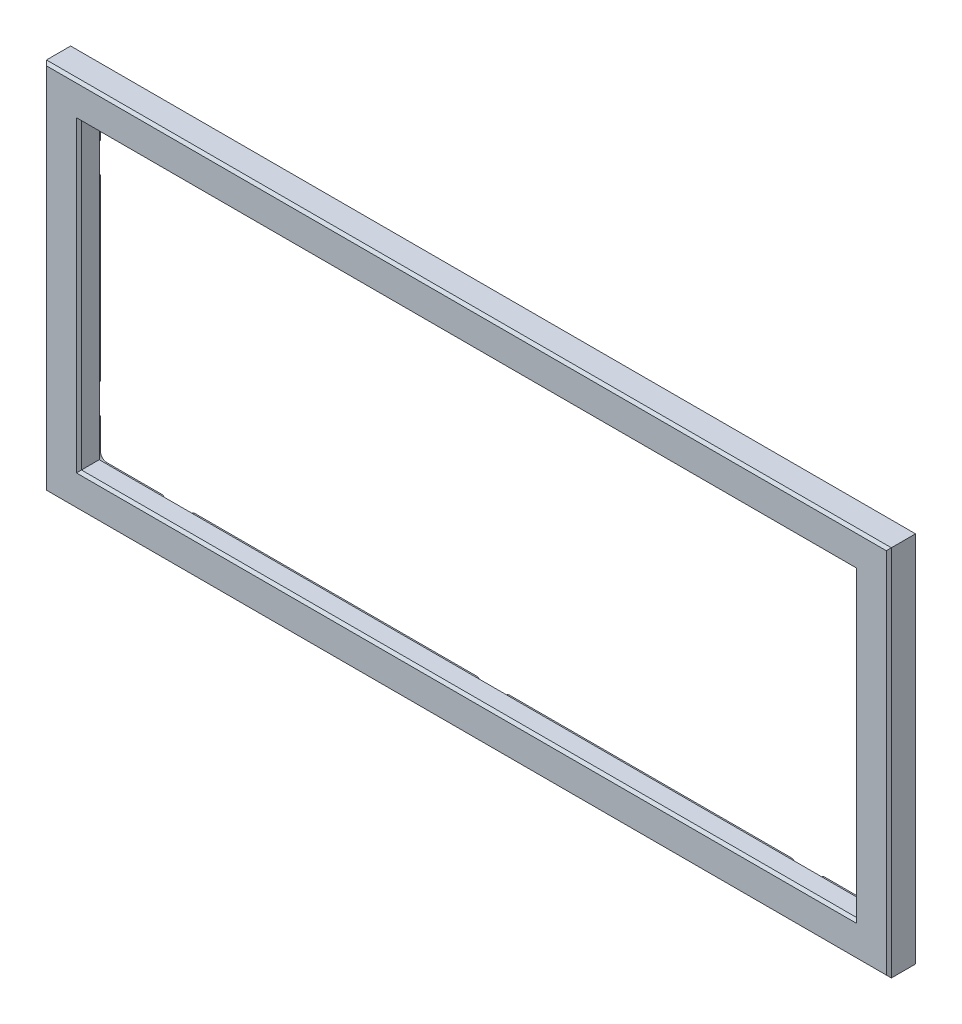
SolidWorks part; units mm, degrees
material "7075-T6 (SN)"
ref_plane "Front Plane" through (0, 0, 0) normal (0, 0, 1) x (1, 0, 0)
ref_plane "Top Plane" through (0, 0, 0) normal (0, 1, 0) x (1, 0, 0)
ref_plane "Right Plane" through (0, 0, 0) normal (1, 0, 0) x (0, 0, -1)
sketch "Sketch1" plane through (0, 0, 0) normal (0, 0, 1) x (1, 0, 0)
  line L43 (-4.2125, 142.325) -> (328.0625, 142.325)
  line L44 (-4.2125, 142.325) -> (-4.2125, -4.2125)
  line L45 (-4.2125, -4.2125) -> (328.0625, -4.2125)
  line L46 (328.0625, 142.325) -> (328.0625, -4.2125)
  line L104 (313.8, 130.5625) -> (292.3, 130.5625)
  line L105 (290.8, 132.0625) -> (290.8, 132.5625)
  line L106 (280.8, 132.5625) -> (280.8, 132.0625)
  line L107 (279.3, 130.5625) -> (168.425, 130.5625)
  line L108 (166.925, 132.0625) -> (166.925, 132.5625)
  line L109 (156.925, 132.5625) -> (156.925, 132.0625)
  line L110 (155.425, 130.5625) -> (44.55, 130.5625)
  line L111 (43.05, 132.0625) -> (43.05, 132.5625)
  line L112 (33.05, 132.5625) -> (33.05, 132.0625)
  line L113 (31.55, 130.5625) -> (10.05, 130.5625)
  line L114 (7.55, 128.0625) -> (7.55, 116.5625)
  line L115 (6.05, 115.0625) -> (5.55, 115.0625)
  line L116 (5.55, 105.0625) -> (6.05, 105.0625)
  line L117 (7.55, 103.5625) -> (7.55, 34.55)
  line L118 (6.05, 33.05) -> (5.55, 33.05)
  line L119 (5.55, 23.05) -> (6.05, 23.05)
  line L120 (7.55, 21.55) -> (7.55, 10.05)
  line L121 (10.05, 7.55) -> (31.55, 7.55)
  line L122 (33.05, 6.05) -> (33.05, 5.55)
  line L123 (43.05, 5.55) -> (43.05, 6.05)
  line L124 (44.55, 7.55) -> (155.425, 7.55)
  line L125 (156.925, 6.05) -> (156.925, 5.55)
  line L126 (166.925, 5.55) -> (166.925, 6.05)
  line L127 (168.425, 7.55) -> (279.3, 7.55)
  line L128 (280.8, 6.05) -> (280.8, 5.55)
  line L129 (290.8, 5.55) -> (290.8, 6.05)
  line L130 (292.3, 7.55) -> (313.8, 7.55)
  line L131 (316.3, 10.05) -> (316.3, 21.55)
  line L132 (317.8, 23.05) -> (318.3, 23.05)
  line L133 (318.3, 33.05) -> (317.8, 33.05)
  line L134 (316.3, 34.55) -> (316.3, 103.5625)
  line L135 (317.8, 105.0625) -> (318.3, 105.0625)
  line L136 (318.3, 115.0625) -> (317.8, 115.0625)
  line L137 (316.3, 116.5625) -> (316.3, 128.0625)
  line L138 (313.8, 130.5625) -> (292.3, 130.5625)
  line L139 (290.8, 132.0625) -> (290.8, 132.5625)
  line L140 (280.8, 132.5625) -> (280.8, 132.0625)
  line L141 (279.3, 130.5625) -> (168.425, 130.5625)
  line L142 (166.925, 132.0625) -> (166.925, 132.5625)
  line L143 (156.925, 132.5625) -> (156.925, 132.0625)
  line L144 (155.425, 130.5625) -> (44.55, 130.5625)
  line L145 (43.05, 132.0625) -> (43.05, 132.5625)
  line L146 (33.05, 132.5625) -> (33.05, 132.0625)
  line L147 (31.55, 130.5625) -> (10.05, 130.5625)
  line L148 (7.55, 128.0625) -> (7.55, 116.5625)
  line L149 (6.05, 115.0625) -> (5.55, 115.0625)
  line L150 (5.55, 105.0625) -> (6.05, 105.0625)
  line L151 (7.55, 103.5625) -> (7.55, 34.55)
  line L152 (6.05, 33.05) -> (5.55, 33.05)
  line L153 (5.55, 23.05) -> (6.05, 23.05)
  line L154 (7.55, 21.55) -> (7.55, 10.05)
  line L155 (10.05, 7.55) -> (31.55, 7.55)
  line L156 (33.05, 6.05) -> (33.05, 5.55)
  line L157 (43.05, 5.55) -> (43.05, 6.05)
  line L158 (44.55, 7.55) -> (155.425, 7.55)
  line L159 (156.925, 6.05) -> (156.925, 5.55)
  line L160 (166.925, 5.55) -> (166.925, 6.05)
  line L161 (168.425, 7.55) -> (279.3, 7.55)
  line L162 (280.8, 6.05) -> (280.8, 5.55)
  line L163 (290.8, 5.55) -> (290.8, 6.05)
  line L164 (292.3, 7.55) -> (313.8, 7.55)
  line L165 (316.3, 10.05) -> (316.3, 21.55)
  line L166 (317.8, 23.05) -> (318.3, 23.05)
  line L167 (318.3, 33.05) -> (317.8, 33.05)
  line L168 (316.3, 34.55) -> (316.3, 103.5625)
  line L169 (317.8, 105.0625) -> (318.3, 105.0625)
  line L170 (318.3, 115.0625) -> (317.8, 115.0625)
  line L171 (316.3, 116.5625) -> (316.3, 128.0625)
  arc A136 (290.8, 132.0625) -> (292.3, 130.5625) centre (292.3, 132.0625) ccw
  arc A137 (290.8, 132.5625) -> (280.8, 132.5625) centre (285.8, 132.5625) ccw
  arc A138 (279.3, 130.5625) -> (280.8, 132.0625) centre (279.3, 132.0625) ccw
  arc A139 (166.925, 132.0625) -> (168.425, 130.5625) centre (168.425, 132.0625) ccw
  arc A140 (166.925, 132.5625) -> (156.925, 132.5625) centre (161.925, 132.5625) ccw
  arc A141 (155.425, 130.5625) -> (156.925, 132.0625) centre (155.425, 132.0625) ccw
  arc A142 (43.05, 132.0625) -> (44.55, 130.5625) centre (44.55, 132.0625) ccw
  arc A143 (43.05, 132.5625) -> (33.05, 132.5625) centre (38.05, 132.5625) ccw
  arc A144 (31.55, 130.5625) -> (33.05, 132.0625) centre (31.55, 132.0625) ccw
  arc A145 (10.05, 130.5625) -> (7.55, 128.0625) centre (10.05, 128.0625) ccw
  arc A146 (6.05, 115.0625) -> (7.55, 116.5625) centre (6.05, 116.5625) ccw
  arc A147 (5.55, 115.0625) -> (5.55, 105.0625) centre (5.55, 110.0625) ccw
  arc A148 (7.55, 103.5625) -> (6.05, 105.0625) centre (6.05, 103.5625) ccw
  arc A149 (6.05, 33.05) -> (7.55, 34.55) centre (6.05, 34.55) ccw
  arc A150 (5.55, 33.05) -> (5.55, 23.05) centre (5.55, 28.05) ccw
  arc A151 (7.55, 21.55) -> (6.05, 23.05) centre (6.05, 21.55) ccw
  arc A152 (7.55, 10.05) -> (10.05, 7.55) centre (10.05, 10.05) ccw
  arc A153 (33.05, 6.05) -> (31.55, 7.55) centre (31.55, 6.05) ccw
  arc A154 (33.05, 5.55) -> (43.05, 5.55) centre (38.05, 5.55) ccw
  arc A155 (44.55, 7.55) -> (43.05, 6.05) centre (44.55, 6.05) ccw
  arc A156 (156.925, 6.05) -> (155.425, 7.55) centre (155.425, 6.05) ccw
  arc A157 (156.925, 5.55) -> (166.925, 5.55) centre (161.925, 5.55) ccw
  arc A158 (168.425, 7.55) -> (166.925, 6.05) centre (168.425, 6.05) ccw
  arc A159 (280.8, 6.05) -> (279.3, 7.55) centre (279.3, 6.05) ccw
  arc A160 (280.8, 5.55) -> (290.8, 5.55) centre (285.8, 5.55) ccw
  arc A161 (292.3, 7.55) -> (290.8, 6.05) centre (292.3, 6.05) ccw
  arc A162 (313.8, 7.55) -> (316.3, 10.05) centre (313.8, 10.05) ccw
  arc A163 (317.8, 23.05) -> (316.3, 21.55) centre (317.8, 21.55) ccw
  arc A164 (318.3, 23.05) -> (318.3, 33.05) centre (318.3, 28.05) ccw
  arc A165 (316.3, 34.55) -> (317.8, 33.05) centre (317.8, 34.55) ccw
  arc A166 (317.8, 105.0625) -> (316.3, 103.5625) centre (317.8, 103.5625) ccw
  arc A167 (318.3, 105.0625) -> (318.3, 115.0625) centre (318.3, 110.0625) ccw
  arc A168 (316.3, 116.5625) -> (317.8, 115.0625) centre (317.8, 116.5625) ccw
  arc A169 (316.3, 128.0625) -> (313.8, 130.5625) centre (313.8, 128.0625) ccw
  arc A170 (290.8, 132.0625) -> (292.3, 130.5625) centre (292.3, 132.0625) ccw
  arc A171 (290.8, 132.5625) -> (280.8, 132.5625) centre (285.8, 132.5625) ccw
  arc A172 (279.3, 130.5625) -> (280.8, 132.0625) centre (279.3, 132.0625) ccw
  arc A173 (166.925, 132.0625) -> (168.425, 130.5625) centre (168.425, 132.0625) ccw
  arc A174 (166.925, 132.5625) -> (156.925, 132.5625) centre (161.925, 132.5625) ccw
  arc A175 (155.425, 130.5625) -> (156.925, 132.0625) centre (155.425, 132.0625) ccw
  arc A176 (43.05, 132.0625) -> (44.55, 130.5625) centre (44.55, 132.0625) ccw
  arc A177 (43.05, 132.5625) -> (33.05, 132.5625) centre (38.05, 132.5625) ccw
  arc A178 (31.55, 130.5625) -> (33.05, 132.0625) centre (31.55, 132.0625) ccw
  arc A179 (10.05, 130.5625) -> (7.55, 128.0625) centre (10.05, 128.0625) ccw
  arc A180 (6.05, 115.0625) -> (7.55, 116.5625) centre (6.05, 116.5625) ccw
  arc A181 (5.55, 115.0625) -> (5.55, 105.0625) centre (5.55, 110.0625) ccw
  arc A182 (7.55, 103.5625) -> (6.05, 105.0625) centre (6.05, 103.5625) ccw
  arc A183 (6.05, 33.05) -> (7.55, 34.55) centre (6.05, 34.55) ccw
  arc A184 (5.55, 33.05) -> (5.55, 23.05) centre (5.55, 28.05) ccw
  arc A185 (7.55, 21.55) -> (6.05, 23.05) centre (6.05, 21.55) ccw
  arc A186 (7.55, 10.05) -> (10.05, 7.55) centre (10.05, 10.05) ccw
  arc A187 (33.05, 6.05) -> (31.55, 7.55) centre (31.55, 6.05) ccw
  arc A188 (33.05, 5.55) -> (43.05, 5.55) centre (38.05, 5.55) ccw
  arc A189 (44.55, 7.55) -> (43.05, 6.05) centre (44.55, 6.05) ccw
  arc A190 (156.925, 6.05) -> (155.425, 7.55) centre (155.425, 6.05) ccw
  arc A191 (156.925, 5.55) -> (166.925, 5.55) centre (161.925, 5.55) ccw
  arc A192 (168.425, 7.55) -> (166.925, 6.05) centre (168.425, 6.05) ccw
  arc A193 (280.8, 6.05) -> (279.3, 7.55) centre (279.3, 6.05) ccw
  arc A194 (280.8, 5.55) -> (290.8, 5.55) centre (285.8, 5.55) ccw
  arc A195 (292.3, 7.55) -> (290.8, 6.05) centre (292.3, 6.05) ccw
  arc A196 (313.8, 7.55) -> (316.3, 10.05) centre (313.8, 10.05) ccw
  arc A197 (317.8, 23.05) -> (316.3, 21.55) centre (317.8, 21.55) ccw
  arc A198 (318.3, 23.05) -> (318.3, 33.05) centre (318.3, 28.05) ccw
  arc A199 (316.3, 34.55) -> (317.8, 33.05) centre (317.8, 34.55) ccw
  arc A200 (317.8, 105.0625) -> (316.3, 103.5625) centre (317.8, 103.5625) ccw
  arc A201 (318.3, 105.0625) -> (318.3, 115.0625) centre (318.3, 110.0625) ccw
  arc A202 (316.3, 116.5625) -> (317.8, 115.0625) centre (317.8, 116.5625) ccw
  arc A203 (316.3, 128.0625) -> (313.8, 130.5625) centre (313.8, 128.0625) ccw
  dimension "D2" = 4.7625
  dimension "D3" = 4.7625
  dimension "D4" = 4.7625
  dimension "D5" = 4.7625
extrude "Boss-Extrude1" add sketch "Sketch1" against normal mid plane 2.5
sketch "Sketch2" plane through (0, 0, 1.25) normal (0, 0, 1) x (1, 0, 0)
  line L28 (7.55, 128.0625) -> (7.55, 116.5625) construction
  line L30 (161.925, 142.325) -> (161.925, -4.2125) construction
  line L31 (-4.2125, 69.0562) -> (328.0625, 69.0562) construction
  line L32 (328.0625, -4.2125) -> (328.0625, 142.325) construction
  line L36 (328.0625, 142.325) -> (-4.2125, 142.325)
  line L38 (-4.2125, 142.325) -> (-4.2125, -4.2125)
  line L39 (9.55, 128.5625) -> (314.3, 128.5625)
  line L40 (-4.2125, -4.2125) -> (328.0625, -4.2125)
  line L41 (9.55, 128.5625) -> (9.55, 9.55)
  line L42 (328.0625, -4.2125) -> (328.0625, 142.325)
  line L43 (9.55, 9.55) -> (314.3, 9.55)
  line L44 (328.0625, 142.325) -> (-4.2125, 142.325)
  line L46 (-4.2125, 142.325) -> (-4.2125, -4.2125)
  line L48 (-4.2125, -4.2125) -> (328.0625, -4.2125)
  line L50 (328.0625, -4.2125) -> (328.0625, 142.325)
  line L52 (314.3, 128.5625) -> (314.3, 9.55)
  dimension "D2" = 11.7625
  dimension "D3" = 13.7625
  dimension "D4" = 13.7625
  dimension "D5" = 13.7625
  dimension "D6" = 13.7625
extrude "Boss-Extrude2" add sketch "Sketch2" along normal blind 8
chamfer "Chamfer1" distance 1 angle 45 8 edges at (328.0625, 69.0562, 9.25) (161.925, -4.2125, 9.25) (-4.2125, 69.0562, 9.25) (161.925, 142.325, 9.25) (9.55, 69.0562, 9.25) (161.925, 9.55, 9.25) (314.3, 69.0562, 9.25) (161.925, 128.5625, 9.25)
hole_wizard "M2.5 Tapped Hole1" positions "Sketch3" profile "Sketch4" tap size "M2.5" standard "DIN"
sketch "Sketch3" plane through (0, 0, 1.25) normal (0, 0, -1) x (-1, 0, 0)
  arc A1 (-290.8, 5.55) -> (-280.8, 5.55) centre (-285.8, 5.55) ccw construction
  point P37 (-285.8, 132.5625)
  point P40 (-318.3, 110.0625)
  point P43 (-318.3, 28.05)
  point P46 (-285.8, 5.55)
  point P49 (-161.925, 5.55)
  point P52 (-38.05, 5.55)
  point P55 (-5.55, 28.05)
  point P58 (-38.05, 132.5625)
  point P61 (-5.55, 110.0625)
  point P65 (-161.925, 132.5625)
sketch "Sketch4" plane through (285.8, 132.5625, 1.25) normal (1, 0, 0) x (0, 1, 0)
  line L0 (0, 0) -> (0, 6.9659)
  line L1 (0, 6.9659) -> (1.025, 6.35)
  line L2 (1.025, 6.35) -> (1.025, 0)
  line L5 (1.025, 0) -> (0, 0)
  line L10 (0, 6.9659) -> (-1.025, 6.35) construction
  line L11 (0, -6.35) -> (0, 107.95) construction
  dimension "Tap Drill Dia." = 2.05
  dimension "Tap Drill Depth" = 6.35
  dimension "Drill Angle" = 118
cosmetic thread "Hole Thread2" parameters "D1"=5, "D2"=3.05
cosmetic thread "Hole Thread3" parameters "D1"=5, "D2"=3.05
cosmetic thread "Hole Thread4" parameters "D1"=5, "D2"=3.05
cosmetic thread "Hole Thread5" parameters "D1"=5, "D2"=3.05
cosmetic thread "Hole Thread6" parameters "D1"=5, "D2"=3.05
cosmetic thread "Hole Thread7" parameters "D1"=5, "D2"=3.05
cosmetic thread "Hole Thread8" parameters "D1"=5, "D2"=3.05
cosmetic thread "Hole Thread9" parameters "D1"=5, "D2"=3.05
cosmetic thread "Hole Thread10" parameters "D1"=5, "D2"=3.05
cosmetic thread "Hole Thread11" parameters "D1"=5, "D2"=3.05
equation "\"D2@Sketch1\"=\"D3@Sketch1\""
equation "\"D4@Sketch1\"=\"D3@Sketch1\""
equation "\"D5@Sketch1\"=\"D3@Sketch1\""
equation "\"D3@Sketch2\"=\"D2@Sketch2\"+2"
equation "\"D4@Sketch2\"=\"D3@Sketch2\""
equation "\"D5@Sketch2\"=\"D3@Sketch2\""
equation "\"D6@Sketch2\"=\"D3@Sketch2\""
